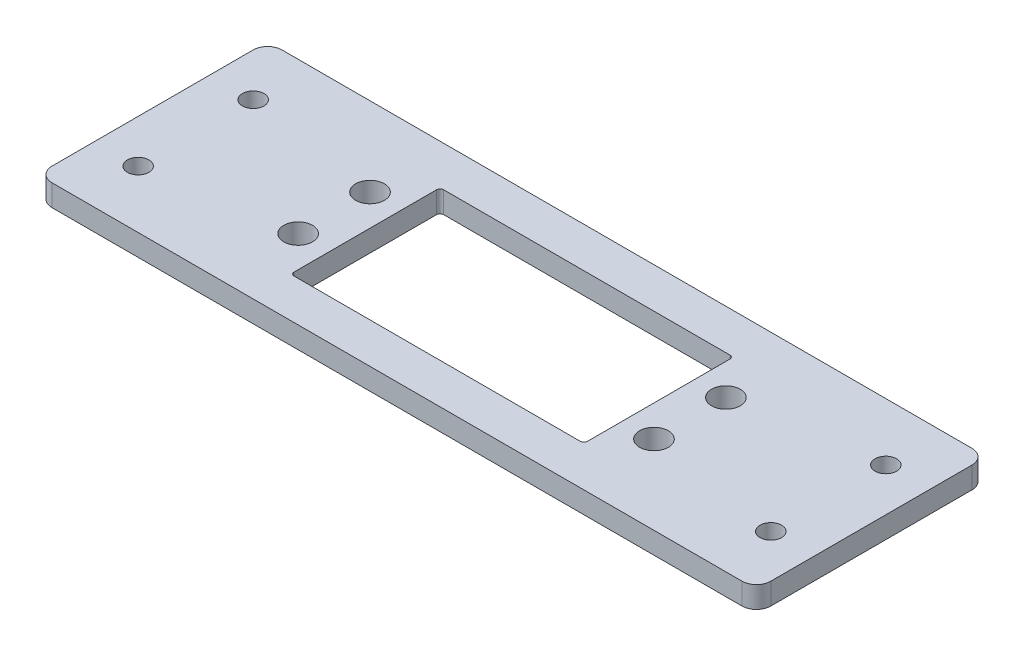
SolidWorks part; units mm, degrees
material "Thornel Mat VMA"
ref_plane "前视基准面" through (0, 0, 0) normal (0, 0, 1) x (1, 0, 0)
ref_plane "上视基准面" through (0, 0, 0) normal (0, 1, 0) x (1, 0, 0)
ref_plane "右视基准面" through (0, 0, 0) normal (1, 0, 0) x (0, 0, -1)
other "Configuration Table"
sketch "草图1" plane through (0, 0, 0) normal (0, 1, 0) x (1, 0, 0)
  line L0 (0, 0) -> (0, 29.6725) construction
  line L1 (-50, -16) -> (50, -16)
  line L2 (-50, -16) -> (-50, 16)
  line L3 (-50, 16) -> (50, 16)
  line L4 (50, -16) -> (50, 16)
  line L5 (-50, -16) -> (50, 16) construction
  line L6 (-50, 16) -> (50, -16) construction
  line L11 (-34.975, -11.192) -> (7.5095, 2.403) construction
  line L13 (-20.4, -10.4) -> (20.4, -10.4)
  line L14 (-20.4, -10.4) -> (-20.4, 10.4)
  line L15 (-20.4, 10.4) -> (20.4, 10.4)
  line L16 (20.4, -10.4) -> (20.4, 10.4)
  line L17 (-20.4, -10.4) -> (20.4, 10.4) construction
  line L18 (-20.4, 10.4) -> (20.4, -10.4) construction
  line L19 (0, 0) -> (43.0948, 0) construction
  circle A0 centre (24.75, 5) radius 2
  circle A1 centre (24.75, -5) radius 2
  circle A2 centre (-24.75, -5) radius 2
  circle A3 centre (-24.75, 5) radius 2
  circle A4 centre (-44, 8) radius 1.5
  circle A5 centre (44, 8) radius 1.5
  circle A6 centre (44, -8) radius 1.5
  circle A7 centre (-44, -8) radius 1.5
  point P0 (0, 0)
  point P6 (0, 0)
  point P13 (0, 0)
  dimension "D5" = 4
  dimension "D8" = 3
  dimension "D1" = 100
  dimension "D2" = 32
  dimension "D3" = 40.8
  dimension "D4" = 20.8
  dimension "D6" = 5
  dimension "D7" = 24.75
  dimension "D9" = 44
  dimension "D10" = 8
extrude "凸台-拉伸1" add sketch "草图1" along normal blind 3
fillet "圆角1" radius 0.5 4 edges at (20.4, 1.5, 10.4) (-20.4, 1.5, 10.4) (20.4, 1.5, -10.4) (-20.4, 1.5, -10.4)
fillet "圆角2" radius 2 4 edges at (50, 1.5, -16) (50, 1.5, 16) (-50, 1.5, -16) (-50, 1.5, 16)
